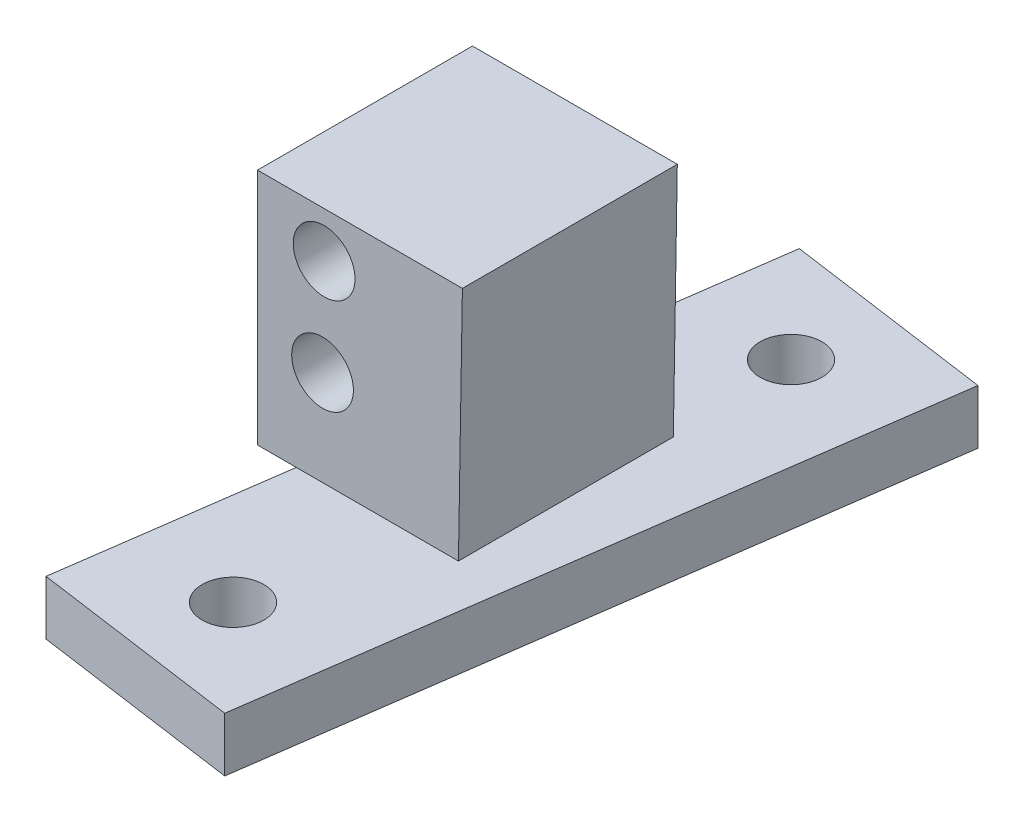
SolidWorks part; units mm, degrees
ref_plane "Front Plane" through (0, 0, 0) normal (0, 0, 1) x (1, 0, 0)
ref_plane "Top Plane" through (0, 0, 0) normal (0, 1, 0) x (1, 0, 0)
ref_plane "Right Plane" through (0, 0, 0) normal (1, 0, 0) x (0, 0, -1)
sketch "Sketch1" plane through (0, 0, 0) normal (0, 0, 1) x (1, 0, 0)
  line L0 (430.4818, 135.1883) -> (451.5463, 135.1883)
  line L1 (426.8731, 135.2483) -> (443.5981, 134.9701) construction
  line L2 (451.5463, 135.1883) -> (451.1391, 110.7021)
  line L3 (451.1391, 110.7021) -> (430.4818, 110.7021)
  line L4 (430.4818, 110.7021) -> (430.4818, 135.1883)
  line L5 (427.9702, 112.9511) -> (437.0368, 112.8004) construction
  line L6 (427.9702, 112.9511) -> (437.0368, 112.8004)
  line L7 (427.9702, 112.9511) -> (437.0368, 112.8004)
  line L8 (427.9702, 112.9511) -> (437.0368, 112.8004)
  line L9 (427.9702, 112.9511) -> (437.0368, 112.8004)
  line L10 (427.9702, 112.9511) -> (437.0368, 112.8004)
  arc A0 (444.3649, 127.3721) -> (443.5981, 134.9701) centre (437.3311, 130.5) ccw construction
  arc A1 (444.3649, 127.3721) -> (444.2998, 123.3969) centre (449.0067, 125.308) ccw construction
  arc A2 (443.2811, 115.8212) -> (444.2998, 123.3969) centre (437.1648, 120.5) ccw construction
  arc A3 (441.8282, 114.3719) -> (443.2811, 115.8212) centre (437.1648, 120.5) ccw construction
  arc A4 (437.0368, 112.8004) -> (441.8282, 114.3719) centre (437.1648, 120.5) ccw construction
  arc A5 (444.3649, 127.3721) -> (443.5981, 134.9701) centre (437.3311, 130.5) ccw
  arc A6 (444.3649, 127.3721) -> (444.2998, 123.3969) centre (449.0067, 125.308) ccw
  arc A7 (443.2811, 115.8212) -> (444.2998, 123.3969) centre (437.1648, 120.5) ccw
  arc A8 (441.8282, 114.3719) -> (443.2811, 115.8212) centre (437.1648, 120.5) ccw
  arc A9 (437.0368, 112.8004) -> (441.8282, 114.3719) centre (437.1648, 120.5) ccw
  circle A10 centre (437.3311, 130.5) radius 3.175
  circle A11 centre (437.1648, 120.5) radius 3.175
extrude "Boss-Extrude1" add sketch "Sketch1" along normal up to surface (22.098 mm away)
ref_plane "Plane1" through (0, 110.7021, 0) normal (0, 1, 0) x (1, 0, 0)
sketch "Sketch2" plane through (0, 110.7021, 0) normal (0, 1, 0) x (1, 0, 0)
  line L0 (431.2956, -44.663) -> (440.8401, 23.2496)
  line L1 (440.8401, 23.2496) -> (462.22, 20.2449)
  line L2 (462.22, 20.2449) -> (452.6755, -47.6677)
  line L3 (452.6755, -47.6677) -> (431.2956, -44.663)
  line L4 (430.4818, -22.098) -> (451.1391, -22.098) construction
  circle A0 centre (443.2228, -37.3619) radius 3.175
  circle A1 centre (450.2928, 12.9438) radius 3.175
  dimension "D5" = 8.89
  dimension "D9" = 6.35
  dimension "D10" = 6.35
  dimension "D1" = 21.59
  dimension "D2" = 68.58
  dimension "D3" = 21.59
  dimension "D4" = 5.08
  dimension "D6" = 8.89
  dimension "D7" = 10.795
  dimension "D8" = 10.795
  dimension "D11" = 98
extrude "Boss-Extrude2" add sketch "Sketch2" against normal blind 5.588
